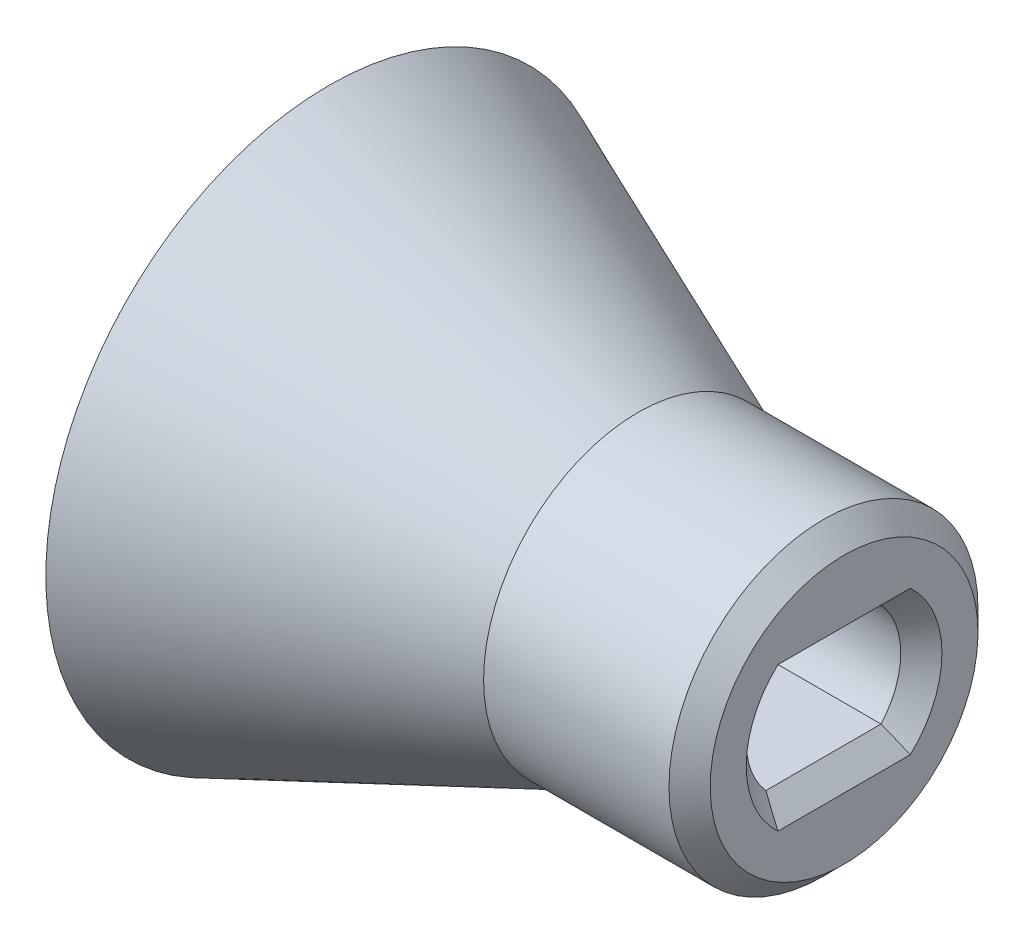
SolidWorks part; units mm, degrees
ref_plane "Front Plane" through (0, 0, 0) normal (0, 0, 1) x (1, 0, 0)
ref_plane "Top Plane" through (0, 0, 0) normal (0, 1, 0) x (1, 0, 0)
ref_plane "Right Plane" through (0, 0, 0) normal (1, 0, 0) x (0, 0, -1)
sketch "Sketch2" plane through (0, 0, 0) normal (0, 0, 1) x (1, 0, 0)
  line L0 (0, 0) -> (0, 11)
  line L1 (0, 11) -> (12, 6)
  line L2 (12, 6) -> (20, 6)
  line L3 (20, 6) -> (20, 0)
  line L4 (20, 0) -> (0, 0)
  dimension "D1" = 12
  dimension "D2" = 11
  dimension "D3" = 6
  dimension "D4" = 8
revolve "Revolve1" add sketch "Sketch2" angle 360 about L4
sketch "Sketch3" plane through (20, 0, 0) normal (1, 0, 0) x (0, 0, -1)
  line L0 (-2.2361, 2) -> (2.2361, 2)
  line L1 (-2.2361, -2) -> (2.2361, -2)
  arc A0 (-2.2361, 2) -> (-2.2361, -2) centre (0, 0) ccw
  arc A1 (2.2361, -2) -> (2.2361, 2) centre (0, 0) ccw
  dimension "D2" = 3
  dimension "D1" = 4
extrude "Cut-Extrude1" cut sketch "Sketch3" against normal blind 8
chamfer "Chamfer1" distance 0.8 angle 45 5 edges at (20, 0, 3) (20, 2, 0) (20, 0, -3) (20, -2, 0) (20, 6, 0)
